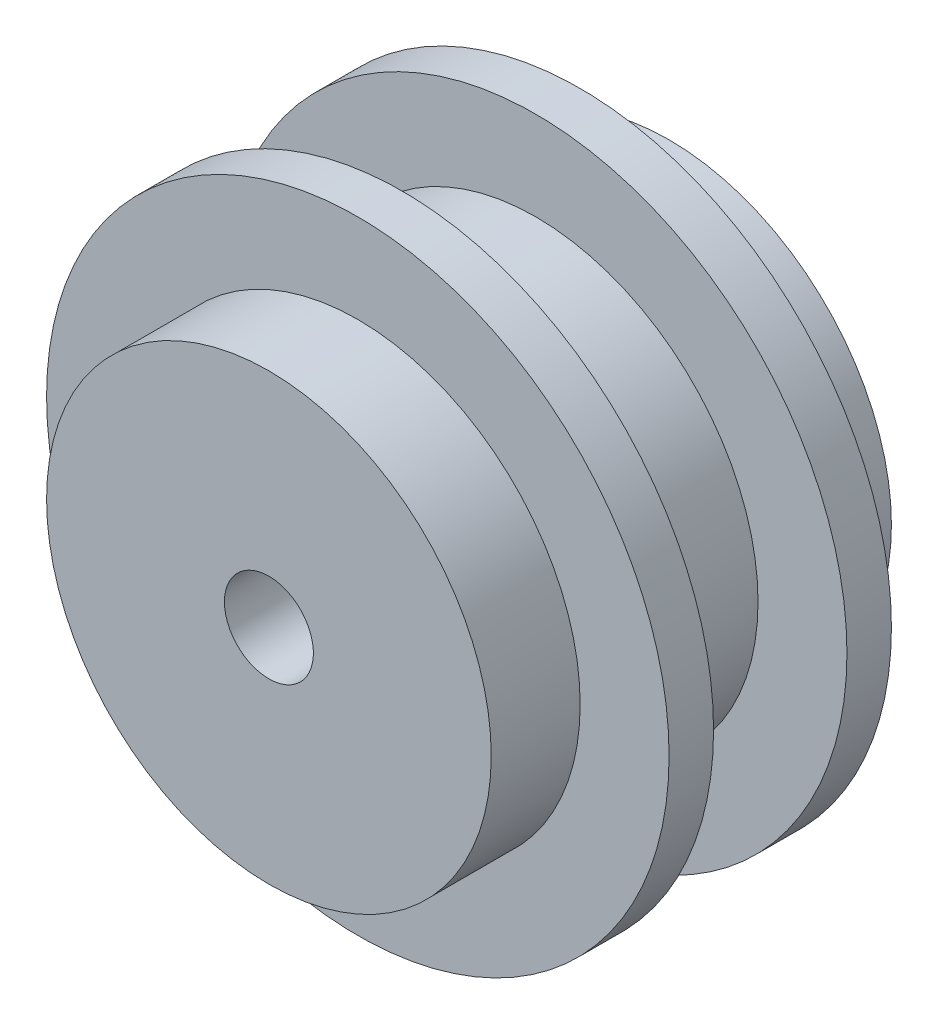
SolidWorks part; units mm, degrees
ref_plane "Front Plane" through (0, 0, 0) normal (0, 0, 1) x (1, 0, 0)
ref_plane "Top Plane" through (0, 0, 0) normal (0, 1, 0) x (1, 0, 0)
ref_plane "Right Plane" through (0, 0, 0) normal (1, 0, 0) x (0, 0, -1)
sketch "Sketch1" plane through (0, 0, 0) normal (1, 0, 0) x (0, 0, -1)
  line L0 (0, 0) -> (0, 250)
  line L1 (0, 0) -> (100, 0)
  line L2 (100, 0) -> (100, -100)
  line L3 (100, -100) -> (150, -100)
  line L4 (150, -100) -> (150, 0)
  line L5 (150, 0) -> (300, 0)
  line L6 (300, 0) -> (300, -100)
  line L7 (300, -100) -> (350, -100)
  line L8 (350, -100) -> (350, 0)
  line L9 (350, 0) -> (450, 0)
  line L10 (450, 0) -> (450, 250)
  line L11 (0, 250) -> (685.0126, 250) construction
  line L12 (0, 250) -> (450, 250)
  dimension "D1" = 250
  dimension "D2" = 100
  dimension "D3" = 50
  dimension "D4" = 50
  dimension "D5" = 150
  dimension "D6" = 100
  dimension "D7" = 100
revolve "Revolve1" add sketch "Sketch1" angle 360 about L11
sketch "Sketch2" plane through (0, 0, -450) normal (0, 0, -1) x (-1, 0, 0)
  circle A0 centre (0, 250) radius 50
  circle A1 centre (0, 250) radius 250 construction
  dimension "D1" = 100
extrude "Cut-Extrude1" cut sketch "Sketch2" against normal through all
